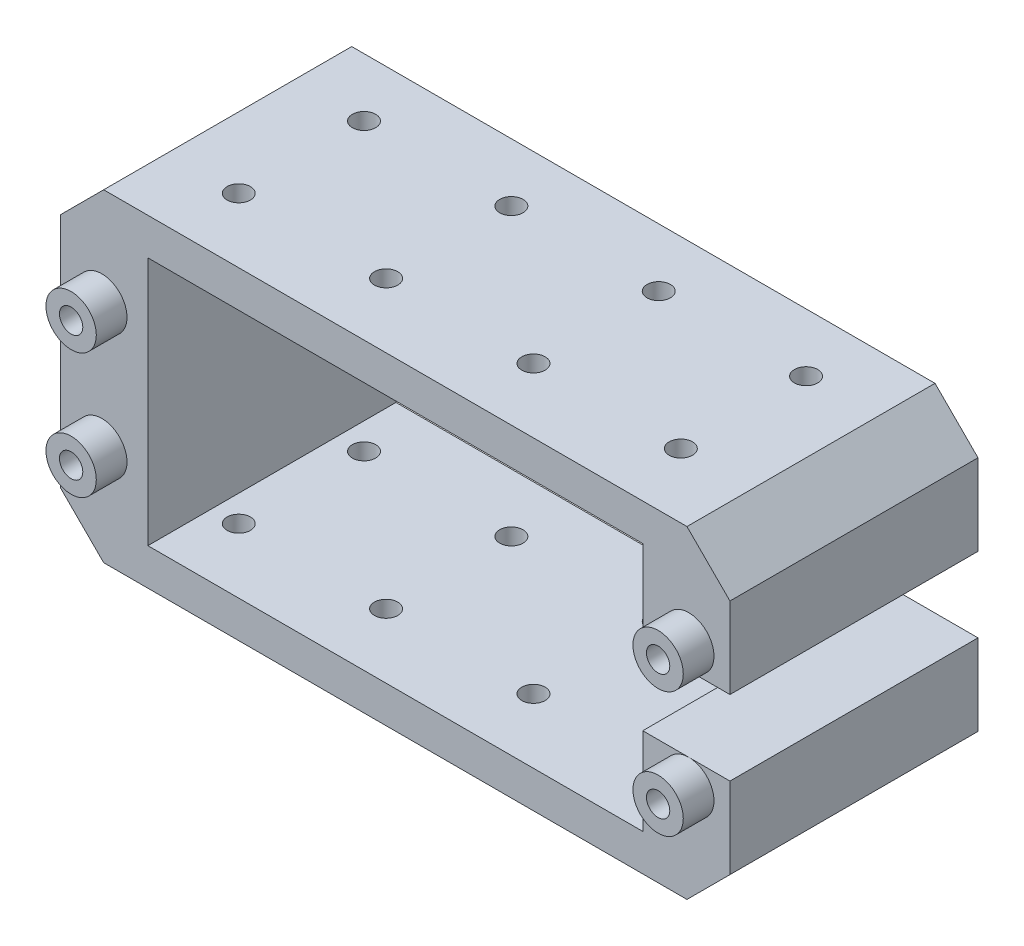
SolidWorks part; units mm, degrees
ref_plane "정면" through (0, 0, 0) normal (0, 0, 1) x (1, 0, 0)
ref_plane "윗면" through (0, 0, 0) normal (0, 1, 0) x (1, 0, 0)
ref_plane "우측면" through (0, 0, 0) normal (1, 0, 0) x (0, 0, -1)
sketch "스케치1" plane through (0, 0, 0) normal (0, 0, 1) x (1, 0, 0)
  line L0 (0, 0) -> (0, 18.6086) construction
  line L1 (-20.15, 10.15) -> (20.15, 10.15)
  line L2 (-20.15, 10.15) -> (-20.15, -10.15)
  line L3 (-20.15, -10.15) -> (20.15, -10.15)
  line L4 (20.15, 10.15) -> (20.15, -10.15)
  line L5 (-20.15, 10.15) -> (20.15, -10.15) construction
  line L6 (-20.15, -10.15) -> (20.15, 10.15) construction
  line L7 (0, 0) -> (23.2455, 0) construction
  line L8 (-27.25, -13.15) -> (27.25, -13.15)
  line L10 (-27.25, 13.15) -> (-27.25, -13.15)
  line L11 (27.25, 13.15) -> (27.25, -13.15)
  line L15 (-27.25, 13.15) -> (27.25, 13.15)
  circle A0 centre (-23.9, 5.1) radius 0.95
  circle A1 centre (23.9, 5.1) radius 0.95
  circle A2 centre (23.9, -5.1) radius 0.95
  circle A3 centre (-23.9, -5.1) radius 0.95
  point P0 (0, 0)
  dimension "D5" = 1.9
  dimension "D1" = 40.3
  dimension "D2" = 20.3
  dimension "D3" = 5.1
  dimension "D4" = 23.9
  dimension "D6" = 54.5
  dimension "D7" = 3
  dimension "D8" = 7.1
extrude "보스-돌출1" add sketch "스케치1" along normal blind 20.2
sketch "스케치2" plane through (0, 0, 20.2) normal (0, 0, 1) x (1, 0, 0)
  circle A0 centre (-23.9, 5.1) radius 2.05
  circle A1 centre (-23.9, -5.1) radius 2.05
  circle A2 centre (23.9, 5.1) radius 2.05
  circle A3 centre (23.9, -5.1) radius 2.05
  circle A4 centre (23.9, -5.1) radius 0.95 construction
  circle A5 centre (23.9, 5.1) radius 0.95 construction
  circle A6 centre (-23.9, -5.1) radius 0.95 construction
  circle A7 centre (-23.9, 5.1) radius 0.95 construction
  circle A8 centre (23.9, -5.1) radius 0.95
  circle A9 centre (23.9, 5.1) radius 0.95
  circle A10 centre (-23.9, -5.1) radius 0.95
  circle A11 centre (-23.9, 5.1) radius 0.95
  dimension "D1" = 4.1
extrude "보스-돌출2" add sketch "스케치2" along normal blind 2.5 contours A0
chamfer "모따기1" distance 3.5 angle 45 4 edges at (-27.25, -13.15, 10.1) (27.25, -13.15, 10.1) (27.25, 13.15, 10.1) (-27.25, 13.15, 10.1)
sketch "스케치3" plane through (0, -13.15, 0) normal (0, -1, 0) x (1, 0, 0)
  line L0 (-40.5712, 14.95) -> (39.8941, 14.95) construction
  line L1 (-23.75, 20.2) -> (23.75, 20.2) construction
  line L2 (0, 20.2) -> (0, 26.1033) construction
  circle A1 centre (-6, 14.95) radius 0.95
  circle A2 centre (6, 14.95) radius 0.95
  circle A3 centre (-18, 14.95) radius 0.95
  circle A4 centre (18, 14.95) radius 0.95
  dimension "D2" = 1.9
  dimension "D1" = 5.25
  dimension "D3" = 12
  dimension "D4" = 12
extrude "컷-돌출1" cut sketch "스케치3" against normal through all
sketch "스케치4" plane through (0, -13.15, 0) normal (0, -1, 0) x (1, 0, 0)
  line L0 (-39.9525, 4.75) -> (39.1582, 4.75) construction
  line L1 (0, 20.2) -> (0, -11.6433) construction
  line L2 (-23.75, 20.2) -> (23.75, 20.2) construction
  line L3 (-23.75, 0) -> (23.75, 0) construction
  circle A0 centre (-6, 4.75) radius 0.95
  circle A1 centre (6, 4.75) radius 0.95
  circle A2 centre (-18, 4.75) radius 0.95
  circle A3 centre (18, 4.75) radius 0.95
  dimension "D2" = 1.9
  dimension "D1" = 4.75
  dimension "D3" = 12
  dimension "D4" = 12
extrude "컷-돌출2" cut sketch "스케치4" against normal through all contours A2
sketch "스케치5" plane through (0, 0, 20.2) normal (0, 0, 1) x (1, 0, 0)
  line L0 (0, 0) -> (37.2295, 0) construction
  line L1 (20.15, 3.05) -> (27.25, 3.05)
  line L2 (20.15, 10.15) -> (20.15, -10.15) construction
  line L3 (27.25, 9.65) -> (27.25, -9.65) construction
  line L4 (20.15, -3.05) -> (27.25, -3.05)
  line L5 (20.15, 3.05) -> (20.15, -3.05)
  line L6 (27.25, 3.05) -> (27.25, -3.05)
  circle A0 centre (23.9, 5.1) radius 2.05 construction
extrude "컷-돌출3" cut sketch "스케치5" against normal through all
